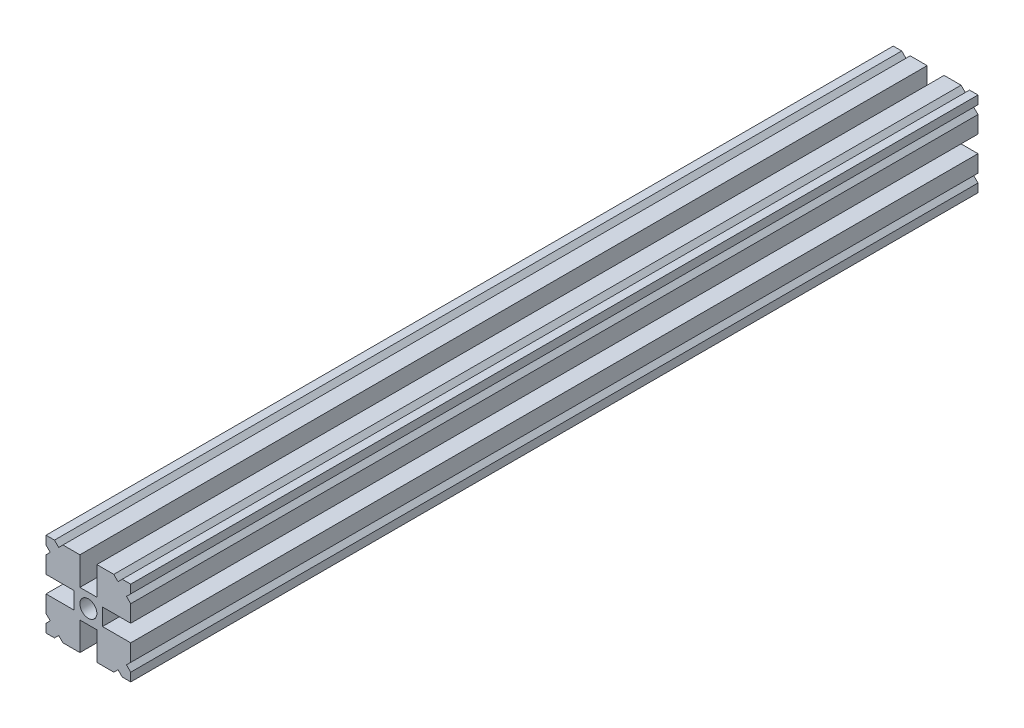
SolidWorks part; units mm, degrees
ref_plane "Front Plane" through (0, 0, 0) normal (0, 0, 1) x (1, 0, 0)
ref_plane "Top Plane" through (0, 0, 0) normal (0, 1, 0) x (1, 0, 0)
ref_plane "Right Plane" through (0, 0, 0) normal (1, 0, 0) x (0, 0, -1)
sketch "Sketch1" plane through (0, 0, 0) normal (0, 0, 1) x (1, 0, 0)
  line L0 (-1.5, 7.5) -> (1.5, 7.5) construction
  line L1 (-7.5, 7.5) -> (7.5, 7.5) construction
  line L2 (-7.5, 7.5) -> (-7.5, -7.5) construction
  line L3 (-7.5, -7.5) -> (7.5, -7.5) construction
  line L4 (7.5, 7.5) -> (7.5, -7.5) construction
  line L5 (-7.5, 7.5) -> (7.5, -7.5) construction
  line L6 (-7.5, -7.5) -> (7.5, 7.5) construction
  line L7 (-7.5, 7.5) -> (-6, 7.5)
  line L8 (7.5, 7.5) -> (6, 7.5)
  line L9 (-6, 7.5) -> (-5.25, 6.75)
  line L10 (-5.25, 6.75) -> (-4.5, 7.5)
  line L11 (-4.5, 7.5) -> (-1.5, 7.5)
  line L12 (-1.5, 7.5) -> (-1.5, 2.5)
  line L13 (-1.5, 2.5) -> (1.5, 2.5)
  line L14 (1.5, 2.5) -> (1.5, 7.5)
  line L15 (1.5, 7.5) -> (4.5, 7.5)
  line L16 (4.5, 7.5) -> (5.25, 6.75)
  line L17 (5.25, 6.75) -> (6, 7.5)
  line L18 (7.5, 7.5) -> (7.5, 6)
  line L19 (7.5, 6) -> (6.75, 5.25)
  line L20 (6.75, 5.25) -> (7.5, 4.5)
  line L21 (7.5, 4.5) -> (7.5, 1.5)
  line L22 (7.5, 1.5) -> (2.5, 1.5)
  line L23 (2.5, 1.5) -> (2.5, -1.5)
  line L24 (2.5, -1.5) -> (7.5, -1.5)
  line L25 (7.5, -1.5) -> (7.5, -4.5)
  line L26 (6.75, -5.25) -> (7.5, -6)
  line L27 (7.5, -4.5) -> (6.75, -5.25)
  line L28 (7.5, -7.5) -> (7.5, -6)
  line L29 (7.5, -7.5) -> (6, -7.5)
  line L30 (6, -7.5) -> (5.25, -6.75)
  line L31 (5.25, -6.75) -> (4.5, -7.5)
  line L32 (4.5, -7.5) -> (1.5, -7.5)
  line L33 (1.5, -7.5) -> (1.5, -2.5)
  line L34 (1.5, -2.5) -> (-1.5, -2.5)
  line L35 (-1.5, -2.5) -> (-1.5, -7.5)
  line L36 (-1.5, -7.5) -> (-4.5, -7.5)
  line L37 (-5.25, -6.75) -> (-6, -7.5)
  line L38 (-4.5, -7.5) -> (-5.25, -6.75)
  line L39 (-7.5, -7.5) -> (-6, -7.5)
  line L40 (-7.5, -7.5) -> (-7.5, -6)
  line L41 (-7.5, -6) -> (-6.75, -5.25)
  line L42 (-6.75, -5.25) -> (-7.5, -4.5)
  line L43 (-7.5, -4.5) -> (-7.5, -1.5)
  line L44 (-7.5, -1.5) -> (-2.5, -1.5)
  line L45 (-2.5, -1.5) -> (-2.5, 1.5)
  line L46 (-2.5, 1.5) -> (-7.5, 1.5)
  line L47 (-7.5, 1.5) -> (-7.5, 4.5)
  line L48 (-6.75, 5.25) -> (-7.5, 6)
  line L49 (-7.5, 4.5) -> (-6.75, 5.25)
  line L50 (-7.5, 7.5) -> (-7.5, 6)
  circle A0 centre (0, 0) radius 1.5
  point P0 (0, 0)
  point P8 (0, 7.5)
  point P56 (0, 0)
  dimension "D8" = 3
  dimension "D1" = 15
  dimension "D2" = 3
  dimension "D3" = 1.5
  dimension "D4" = 5
  dimension "D5" = 1.5
  dimension "D6" = 3
  dimension "D7" = 4
extrude "Boss-Extrude1" add sketch "Sketch1" along normal blind 150
